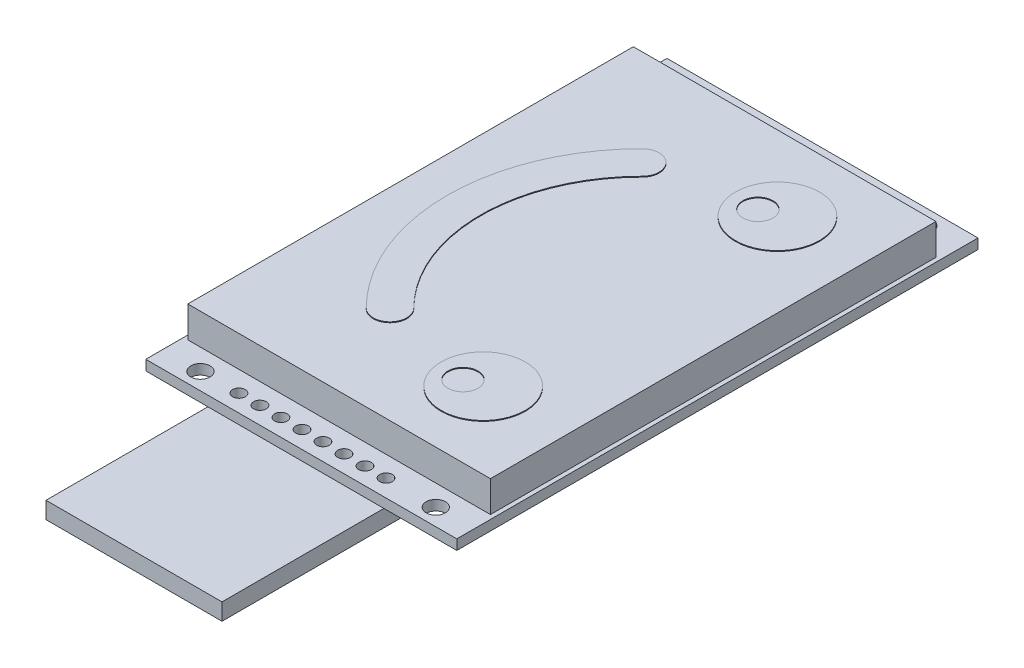
SolidWorks part; units mm, degrees
ref_plane "Front Plane" through (0, 0, 0) normal (0, 0, 1) x (1, 0, 0)
ref_plane "Top Plane" through (0, 0, 0) normal (0, 1, 0) x (1, 0, 0)
ref_plane "Right Plane" through (0, 0, 0) normal (1, 0, 0) x (0, 0, -1)
sketch "Sketch1" plane through (0, 0, 0) normal (0, 1, 0) x (1, 0, 0)
  line L0 (32.5, 60) -> (32.5, 2) construction
  line L1 (0, 0) -> (37, 0)
  line L2 (0, 0) -> (0, 62)
  line L3 (0, 62) -> (37, 62)
  line L4 (37, 0) -> (37, 62)
  line L5 (32.5, 2) -> (4.5, 2) construction
  line L6 (4.5, 2) -> (4.5, 60) construction
  line L7 (4.5, 60) -> (32.5, 60) construction
  line L8 (18.5, 2) -> (18.5, 0) construction
  line L9 (4.5, 31) -> (0, 31) construction
  circle A0 centre (32.5, 60) radius 1.15
  circle A1 centre (4.5, 60) radius 1.15
  circle A2 centre (32.5, 2) radius 1.15
  circle A3 centre (4.5, 2) radius 1.15
  dimension "D3" = 2.3
  dimension "D1" = 37
  dimension "D2" = 62
  dimension "D4" = 28
  dimension "D5" = 58
extrude "Boss-Extrude1" add sketch "Sketch1" along normal blind 1.2
sketch "Sketch2" plane through (0, 1.2, 0) normal (0, 1, 0) x (1, 0, 0)
  line L0 (37, 0) -> (37, 62) construction
  line L1 (0.5, 57.5) -> (36.5, 57.5)
  line L2 (0.5, 57.5) -> (0.5, 4.5)
  line L3 (0.5, 4.5) -> (36.5, 4.5)
  line L4 (36.5, 57.5) -> (36.5, 4.5)
  line L5 (0, 62) -> (0, 0) construction
  line L6 (36.5, 31) -> (37, 31) construction
  dimension "D1" = 0.5
  dimension "D2" = 0.5
  dimension "D3" = 53
extrude "Boss-Extrude2" add sketch "Sketch2" along normal blind 3.7
sketch "Sketch3" plane through (0, 1.2, 0) normal (0, 1, 0) x (1, 0, 0)
  circle A0 centre (9.0316, 2.0507) radius 0.75
  circle A1 centre (11.5316, 2.0507) radius 0.75
  circle A2 centre (14.0316, 2.0507) radius 0.75
  circle A3 centre (16.5316, 2.0507) radius 0.75
  circle A4 centre (19.0316, 2.0507) radius 0.75
  circle A5 centre (21.5316, 2.0507) radius 0.75
  circle A6 centre (24.0316, 2.0507) radius 0.75
  circle A7 centre (26.5316, 2.0507) radius 0.75
  dimension "D1" = 1.5
  dimension "D2" = 8
extrude "Cut-Extrude1" cut sketch "Sketch3" against normal through all
sketch "Sketch4" plane through (0, 4.9, 0) normal (0, 1, 0) x (1, 0, 0)
  line L0 (26.6399, 48.5) -> (26.6399, 13.5) construction
  line L1 (13.0544, 46) -> (13.0544, 16) construction
  line L2 (26.6399, 31) -> (13.0544, 31) construction
  line L3 (36.5, 31) -> (26.6399, 31) construction
  line L4 (36.5, 4.5) -> (36.5, 57.5) construction
  circle A0 centre (26.6399, 48.5) radius 5
  circle A1 centre (26.6399, 13.5) radius 5
  arc A2 (11.6401, 47.4142) -> (11.6401, 14.5858) centre (28.0544, 31) ccw
  arc A3 (14.4686, 44.5858) -> (14.4686, 17.4142) centre (28.0544, 31) ccw
  arc A4 (14.4686, 44.5858) -> (11.6401, 47.4142) centre (13.0544, 46) ccw
  arc A5 (14.4686, 17.4142) -> (11.6401, 14.5858) centre (13.0544, 16) cw
  circle A6 centre (24.7633, 12.9717) radius 1.7861
  circle A7 centre (24.7633, 48.0582) radius 1.7861
  dimension "D1" = 35
  dimension "D2" = 10
  dimension "D4" = 2
  dimension "D3" = 30
  dimension "D5" = 15
extrude "Boss-Extrude3" add sketch "Sketch4" along normal blind 0.1
ref_plane "Plane1" through (0, 0, -31) normal (0, 0, 1) x (1, 0, 0)
sketch "Sketch5" plane through (0, 0, 0) normal (0, -1, 0) x (1, 0, 0)
  line L1 (7.392, -4.4911) -> (28.3291, -4.4911)
  line L2 (7.392, -4.4911) -> (7.392, 19.2584)
  line L3 (7.392, 19.2584) -> (28.3291, 19.2584)
  line L4 (28.3291, -4.4911) -> (28.3291, 19.2584)
extrude "Boss-Extrude4" add sketch "Sketch5" along normal blind 2
